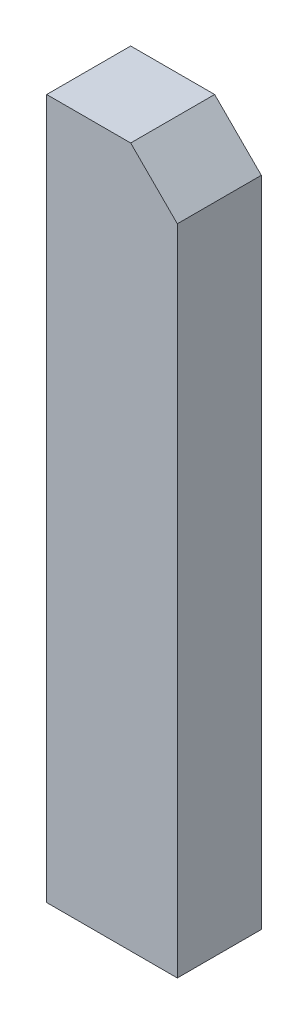
SolidWorks part; units mm, degrees
ref_plane "Front Plane" through (0, 0, 0) normal (0, 0, 1) x (1, 0, 0)
ref_plane "Top Plane" through (0, 0, 0) normal (0, 1, 0) x (1, 0, 0)
ref_plane "Right Plane" through (0, 0, 0) normal (1, 0, 0) x (0, 0, -1)
sketch "Sketch2" plane through (0, 0, 0) normal (0, 1, 0) x (1, 0, 0)
  line L1 (-1.4, -0.9) -> (1.4, -0.9)
  line L2 (-1.4, -0.9) -> (-1.4, 0.9)
  line L3 (-1.4, 0.9) -> (1.4, 0.9)
  line L4 (1.4, -0.9) -> (1.4, 0.9)
  line L5 (-1.4, -0.9) -> (1.4, 0.9) construction
  line L6 (-1.4, 0.9) -> (1.4, -0.9) construction
  point P0 (0, 0)
  dimension "D1" = 1.8
  dimension "D2" = 2.8
extrude "Boss-Extrude1" add sketch "Sketch2" along normal blind 15
chamfer "Chamfer1" distance 1 angle 45 1 edges at (1.4, 15, 0)
